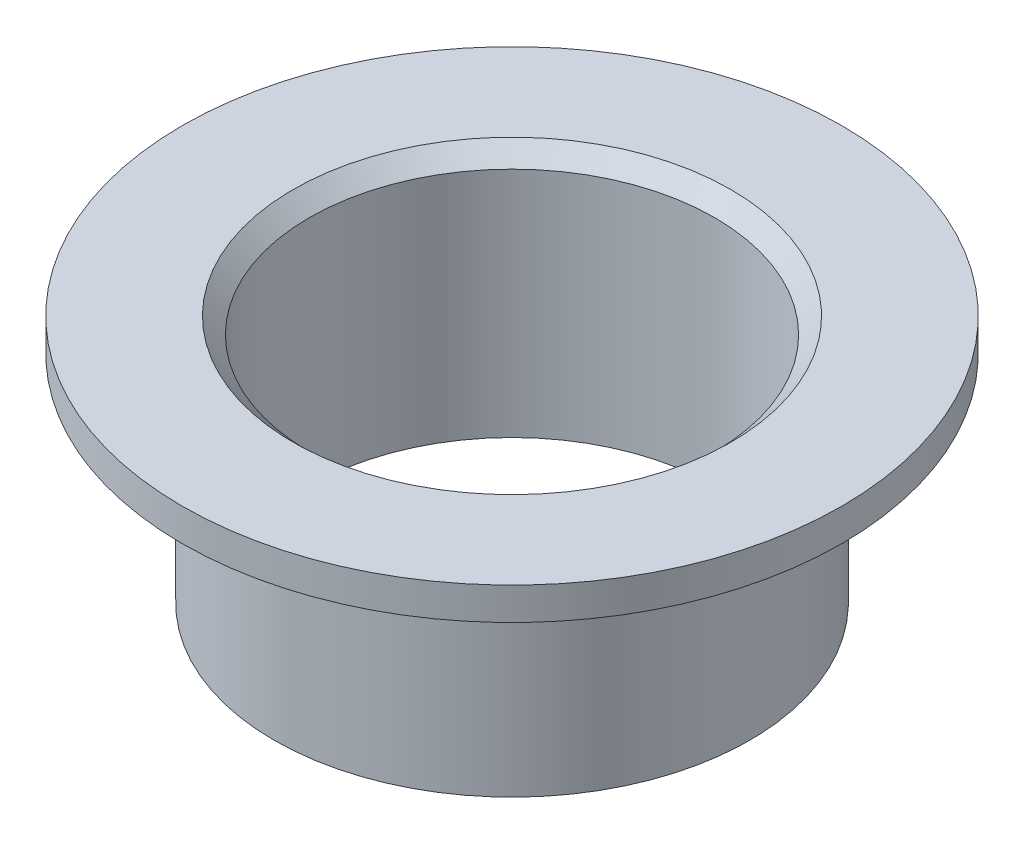
SolidWorks part; units mm, degrees
ref_plane "Front Plane" through (0, 0, 0) normal (0, 0, 1) x (1, 0, 0)
ref_plane "Top Plane" through (0, 0, 0) normal (0, 1, 0) x (1, 0, 0)
ref_plane "Right Plane" through (0, 0, 0) normal (1, 0, 0) x (0, 0, -1)
sketch "Sketch1" plane through (0, 0, 0) normal (0, 0, 1) x (1, 0, 0)
  line L0 (-44, 0) -> (-44, 40)
  line L1 (-37.5, 0) -> (-44, 0)
  line L2 (0, 0) -> (0, 46) construction
  line L3 (-44, 40) -> (-61, 40)
  line L4 (-61, 40) -> (-61, 46)
  line L5 (-61, 46) -> (-37.5, 46)
  line L6 (-37.5, 46) -> (-37.5, 0)
revolve "Revolve1" add sketch "Sketch1" angle 360 about L2
chamfer "Chamfer1" distance 3 angle 45 1 edges at (0, 46, -37.5)
